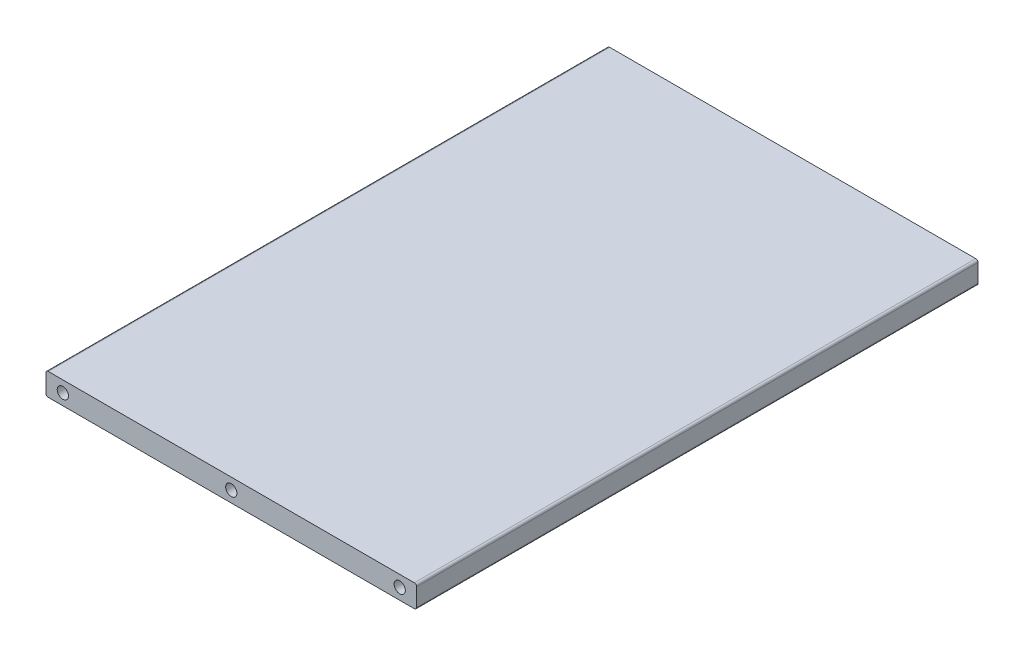
SolidWorks part; units mm, degrees
ref_plane "Front Plane" through (0, 0, 0) normal (0, 0, 1) x (1, 0, 0)
ref_plane "Top Plane" through (0, 0, 0) normal (0, 1, 0) x (1, 0, 0)
ref_plane "Right Plane" through (0, 0, 0) normal (1, 0, 0) x (0, 0, -1)
sketch "Sketch1" plane through (0, 0, 0) normal (0, 1, 0) x (1, 0, 0)
  line L1 (-165, -250) -> (165, -250)
  line L2 (-165, -250) -> (-165, 250)
  line L3 (-165, 250) -> (165, 250)
  line L4 (165, -250) -> (165, 250)
  line L5 (-165, -250) -> (165, 250) construction
  line L6 (-165, 250) -> (165, -250) construction
  point P0 (0, 0)
  dimension "D1" = 330
  dimension "D2" = 500
extrude "Boss-Extrude1" add sketch "Sketch1" along normal blind 20
sketch "Sketch2" plane through (0, 0, 250) normal (0, 0, 1) x (1, 0, 0)
  line L0 (-165, 10) -> (165, 10) construction
  line L1 (-165, 20) -> (-165, 0) construction
  line L2 (165, 20) -> (165, 0) construction
  circle A0 centre (0, 10) radius 5
  circle A1 centre (-150, 10) radius 5
  circle A2 centre (150, 10) radius 5
  dimension "D1" = 10
  dimension "D2" = 150
  dimension "D3" = 150
extrude "Cut-Extrude1" cut sketch "Sketch2" against normal through all
fillet "Fillet1" radius 2 4 edges at (-165, 0, 0) (-165, 20, 0) (165, 0, 0) (165, 20, 0)
